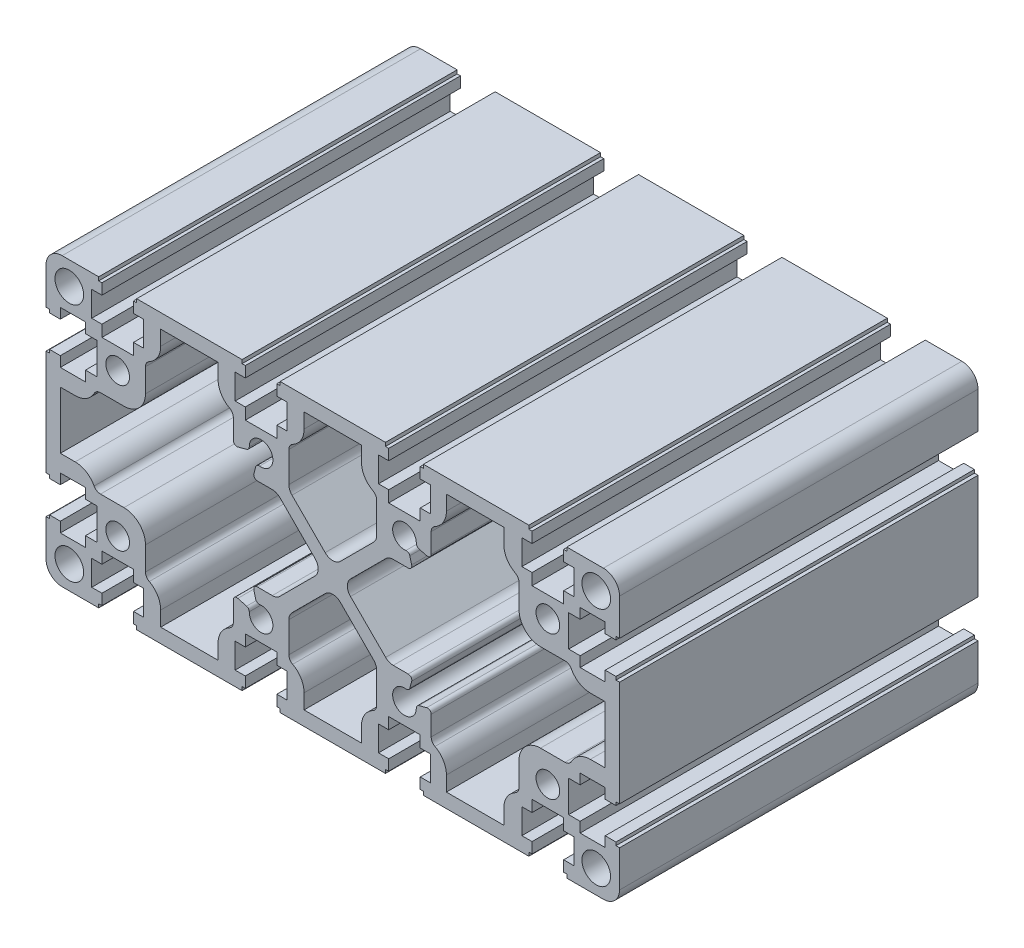
SolidWorks part; units mm, degrees
ref_plane "前视基准面" through (0, 0, 0) normal (0, 0, 1) x (1, 0, 0)
ref_plane "上视基准面" through (0, 0, 0) normal (0, 1, 0) x (1, 0, 0)
ref_plane "右视基准面" through (0, 0, 0) normal (1, 0, 0) x (0, 0, -1)
sketch "草图1" plane through (0, 0, 0) normal (0, 0, 1) x (1, 0, 0)
  line L0 (2688.5545, -1547.2016) -> (2680.1545, -1547.2016)
  line L1 (2558.3545, -1547.2016) -> (2587.7545, -1547.2016)
  line L2 (2537.5545, -1547.2016) -> (2547.7545, -1547.2016)
  line L3 (2533.0545, -1561.9016) -> (2533.0545, -1551.7016)
  line L4 (2533.0545, -1572.5016) -> (2533.0545, -1587.2016)
  line L5 (2548.6545, -1561.4016) -> (2557.4545, -1561.4016)
  line L6 (2557.4545, -1551.2016) -> (2560.3045, -1551.2016)
  line L7 (2548.6545, -1551.2016) -> (2545.8045, -1551.2016)
  line L8 (2558.3545, -1548.2016) -> (2557.4545, -1548.2016)
  line L9 (2548.6545, -1548.2016) -> (2547.7545, -1548.2016)
  line L10 (2548.6545, -1548.2016) -> (2548.6545, -1551.2016)
  line L11 (2557.4545, -1548.2016) -> (2557.4545, -1551.2016)
  line L12 (2547.7545, -1547.2016) -> (2547.7545, -1548.2016)
  line L13 (2558.3545, -1547.2016) -> (2558.3545, -1548.2016)
  line L14 (2545.8045, -1551.2016) -> (2545.8045, -1558.2016)
  line L15 (2560.3045, -1551.2016) -> (2560.3045, -1558.2016)
  line L16 (2545.8045, -1558.2016) -> (2548.6545, -1558.2016)
  line L17 (2557.4545, -1558.2016) -> (2560.3045, -1558.2016)
  line L18 (2557.4545, -1561.4016) -> (2557.4545, -1558.2016)
  line L19 (2548.6545, -1561.4016) -> (2548.6545, -1558.2016)
  line L20 (2592.0077, -1574.4016) -> (2597.426, -1574.4016)
  line L21 (2667.1545, -1547.2016) -> (2638.3545, -1547.2016)
  line L22 (2688.5545, -1547.2016) -> (2678.3545, -1547.2016)
  line L23 (2667.7545, -1547.2016) -> (2638.3545, -1547.2016)
  line L24 (2677.4545, -1561.4016) -> (2668.6545, -1561.4016)
  line L25 (2668.6545, -1551.2016) -> (2665.8045, -1551.2016)
  line L26 (2677.4545, -1551.2016) -> (2680.3045, -1551.2016)
  line L27 (2667.7545, -1548.2016) -> (2668.6545, -1548.2016)
  line L28 (2677.4545, -1548.2016) -> (2678.3545, -1548.2016)
  line L29 (2677.4545, -1548.2016) -> (2677.4545, -1551.2016)
  line L30 (2668.6545, -1548.2016) -> (2668.6545, -1551.2016)
  line L31 (2678.3545, -1547.2016) -> (2678.3545, -1548.2016)
  line L32 (2667.7545, -1547.2016) -> (2667.7545, -1548.2016)
  line L33 (2680.3045, -1551.2016) -> (2680.3045, -1558.2016)
  line L34 (2665.8045, -1551.2016) -> (2665.8045, -1558.2016)
  line L35 (2680.3045, -1558.2016) -> (2677.4545, -1558.2016)
  line L36 (2668.6545, -1558.2016) -> (2665.8045, -1558.2016)
  line L37 (2668.6545, -1561.4016) -> (2668.6545, -1558.2016)
  line L38 (2677.4545, -1561.4016) -> (2677.4545, -1558.2016)
  line L39 (2598.3545, -1547.2016) -> (2627.7545, -1547.2016)
  line L40 (2565.0545, -1551.2016) -> (2581.0545, -1551.2016)
  line L41 (2560.8045, -1568.9516) -> (2560.8045, -1562.4016)
  line L42 (2565.0545, -1555.335) -> (2565.0545, -1551.2016)
  line L43 (2585.3045, -1567.952) -> (2585.3045, -1562.4016)
  line L44 (2581.0545, -1555.335) -> (2581.0545, -1551.2016)
  line L45 (2547.2545, -1571.6016) -> (2547.2545, -1562.8016)
  line L46 (2537.0545, -1562.8016) -> (2537.0545, -1559.9516)
  line L47 (2537.0545, -1571.6016) -> (2537.0545, -1574.4516)
  line L48 (2534.0545, -1561.9016) -> (2534.0545, -1562.8016)
  line L49 (2534.0545, -1571.6016) -> (2534.0545, -1572.5016)
  line L50 (2534.0545, -1571.6016) -> (2537.0545, -1571.6016)
  line L51 (2534.0545, -1562.8016) -> (2537.0545, -1562.8016)
  line L52 (2533.0545, -1572.5016) -> (2534.0545, -1572.5016)
  line L53 (2533.0545, -1561.9016) -> (2534.0545, -1561.9016)
  line L54 (2537.0545, -1574.4516) -> (2544.0545, -1574.4516)
  line L55 (2537.0545, -1559.9516) -> (2544.0545, -1559.9516)
  line L56 (2544.0545, -1574.4516) -> (2544.0545, -1571.6016)
  line L57 (2544.0545, -1562.8016) -> (2544.0545, -1559.9516)
  line L58 (2547.2545, -1562.8016) -> (2544.0545, -1562.8016)
  line L59 (2547.2545, -1571.6016) -> (2544.0545, -1571.6016)
  line L60 (2537.0545, -1587.2016) -> (2537.0545, -1579.2016)
  line L61 (2554.8045, -1574.9516) -> (2548.2545, -1574.9516)
  line L62 (2541.1878, -1579.2016) -> (2537.0545, -1579.2016)
  line L63 (2610.226, -1587.2016) -> (2597.426, -1600.0016)
  line L64 (2613.0545, -1584.3732) -> (2625.3045, -1572.1232)
  line L65 (2628.6829, -1574.4016) -> (2615.8829, -1587.2016)
  line L66 (2613.0545, -1590.03) -> (2600.8045, -1602.28)
  line L67 (2610.226, -1587.2016) -> (2597.426, -1574.4016)
  line L68 (2613.0545, -1590.03) -> (2625.3045, -1602.28)
  line L69 (2613.0545, -1584.3732) -> (2600.8045, -1572.1232)
  line L70 (2615.8829, -1587.2016) -> (2628.6829, -1600.0016)
  line L71 (2693.0545, -1572.5016) -> (2693.0545, -1587.2016)
  line L72 (2665.0045, -1568.9516) -> (2665.0045, -1562.4016)
  line L73 (2678.8545, -1571.6016) -> (2678.8545, -1562.8016)
  line L74 (2689.0545, -1562.8016) -> (2689.0545, -1559.9516)
  line L75 (2689.0545, -1571.6016) -> (2689.0545, -1574.4516)
  line L76 (2692.0545, -1561.9016) -> (2692.0545, -1562.8016)
  line L77 (2692.0545, -1571.6016) -> (2692.0545, -1572.5016)
  line L78 (2692.0545, -1571.6016) -> (2689.0545, -1571.6016)
  line L79 (2692.0545, -1562.8016) -> (2689.0545, -1562.8016)
  line L80 (2693.0545, -1572.5016) -> (2692.0545, -1572.5016)
  line L81 (2693.0545, -1561.9016) -> (2692.0545, -1561.9016)
  line L82 (2689.0545, -1574.4516) -> (2682.0545, -1574.4516)
  line L83 (2689.0545, -1559.9516) -> (2682.0545, -1559.9516)
  line L84 (2682.0545, -1574.4516) -> (2682.0545, -1571.6016)
  line L85 (2682.0545, -1562.8016) -> (2682.0545, -1559.9516)
  line L86 (2678.8545, -1562.8016) -> (2682.0545, -1562.8016)
  line L87 (2678.8545, -1571.6016) -> (2682.0545, -1571.6016)
  line L88 (2689.0545, -1587.2016) -> (2689.0545, -1579.2016)
  line L89 (2671.0045, -1574.9516) -> (2677.8545, -1574.9516)
  line L90 (2684.9211, -1579.2016) -> (2689.0545, -1579.2016)
  line L91 (2693.0545, -1551.7016) -> (2693.0545, -1561.9016)
  line L92 (2589.0143, -1568.2611) -> (2586.5633, -1568.9179)
  line L93 (2591.5596, -1571.2101) -> (2591.0418, -1573.1428)
  line L94 (2634.1012, -1574.4016) -> (2628.6829, -1574.4016)
  line L95 (2637.0946, -1568.2611) -> (2639.2457, -1568.8375)
  line L96 (2634.5493, -1571.2101) -> (2635.0672, -1573.1428)
  line L97 (2605.0545, -1551.2016) -> (2621.0545, -1551.2016)
  line L98 (2600.8045, -1572.1232) -> (2600.8045, -1562.4016)
  line L99 (2605.0545, -1555.335) -> (2605.0545, -1551.2016)
  line L100 (2625.3045, -1572.1232) -> (2625.3045, -1562.4016)
  line L101 (2621.0545, -1555.335) -> (2621.0545, -1551.2016)
  line L102 (2644.7545, -1551.2016) -> (2660.7545, -1551.2016)
  line L103 (2640.5045, -1567.8716) -> (2640.5045, -1562.4016)
  line L104 (2644.7545, -1555.335) -> (2644.7545, -1551.2016)
  line L105 (2660.7545, -1555.335) -> (2660.7545, -1551.2016)
  line L106 (2588.6545, -1561.4016) -> (2597.4545, -1561.4016)
  line L107 (2597.4545, -1551.2016) -> (2600.3045, -1551.2016)
  line L108 (2588.6545, -1551.2016) -> (2585.8045, -1551.2016)
  line L109 (2598.3545, -1548.2016) -> (2597.4545, -1548.2016)
  line L110 (2588.6545, -1548.2016) -> (2587.7545, -1548.2016)
  line L111 (2588.6545, -1548.2016) -> (2588.6545, -1551.2016)
  line L112 (2597.4545, -1548.2016) -> (2597.4545, -1551.2016)
  line L113 (2587.7545, -1547.2016) -> (2587.7545, -1548.2016)
  line L114 (2598.3545, -1547.2016) -> (2598.3545, -1548.2016)
  line L115 (2585.8045, -1551.2016) -> (2585.8045, -1558.2016)
  line L116 (2600.3045, -1551.2016) -> (2600.3045, -1558.2016)
  line L117 (2585.8045, -1558.2016) -> (2588.6545, -1558.2016)
  line L118 (2597.4545, -1558.2016) -> (2600.3045, -1558.2016)
  line L119 (2597.4545, -1561.4016) -> (2597.4545, -1558.2016)
  line L120 (2588.6545, -1561.4016) -> (2588.6545, -1558.2016)
  line L121 (2628.6545, -1561.4016) -> (2637.4545, -1561.4016)
  line L122 (2637.4545, -1551.2016) -> (2640.3045, -1551.2016)
  line L123 (2628.6545, -1551.2016) -> (2625.8045, -1551.2016)
  line L124 (2638.3545, -1548.2016) -> (2637.4545, -1548.2016)
  line L125 (2628.6545, -1548.2016) -> (2627.7545, -1548.2016)
  line L126 (2628.6545, -1548.2016) -> (2628.6545, -1551.2016)
  line L127 (2637.4545, -1548.2016) -> (2637.4545, -1551.2016)
  line L128 (2627.7545, -1547.2016) -> (2627.7545, -1548.2016)
  line L129 (2638.3545, -1547.2016) -> (2638.3545, -1548.2016)
  line L130 (2625.8045, -1551.2016) -> (2625.8045, -1558.2016)
  line L131 (2640.3045, -1551.2016) -> (2640.3045, -1558.2016)
  line L132 (2625.8045, -1558.2016) -> (2628.6545, -1558.2016)
  line L133 (2637.4545, -1558.2016) -> (2640.3045, -1558.2016)
  line L134 (2637.4545, -1561.4016) -> (2637.4545, -1558.2016)
  line L135 (2628.6545, -1561.4016) -> (2628.6545, -1558.2016)
  line L136 (2688.5545, -1627.2016) -> (2680.1545, -1627.2016)
  line L137 (2558.3545, -1627.2016) -> (2587.7545, -1627.2016)
  line L138 (2537.5545, -1627.2016) -> (2547.7545, -1627.2016)
  line L139 (2533.0545, -1612.5016) -> (2533.0545, -1622.7016)
  line L140 (2533.0545, -1601.9016) -> (2533.0545, -1587.2016)
  line L141 (2548.6545, -1613.0016) -> (2557.4545, -1613.0016)
  line L142 (2557.4545, -1623.2016) -> (2560.3045, -1623.2016)
  line L143 (2548.6545, -1623.2016) -> (2545.8045, -1623.2016)
  line L144 (2558.3545, -1626.2016) -> (2557.4545, -1626.2016)
  line L145 (2548.6545, -1626.2016) -> (2547.7545, -1626.2016)
  line L146 (2548.6545, -1626.2016) -> (2548.6545, -1623.2016)
  line L147 (2557.4545, -1626.2016) -> (2557.4545, -1623.2016)
  line L148 (2547.7545, -1627.2016) -> (2547.7545, -1626.2016)
  line L149 (2558.3545, -1627.2016) -> (2558.3545, -1626.2016)
  line L150 (2545.8045, -1623.2016) -> (2545.8045, -1616.2016)
  line L151 (2560.3045, -1623.2016) -> (2560.3045, -1616.2016)
  line L152 (2545.8045, -1616.2016) -> (2548.6545, -1616.2016)
  line L153 (2557.4545, -1616.2016) -> (2560.3045, -1616.2016)
  line L154 (2557.4545, -1613.0016) -> (2557.4545, -1616.2016)
  line L155 (2548.6545, -1613.0016) -> (2548.6545, -1616.2016)
  line L156 (2592.0077, -1600.0016) -> (2597.426, -1600.0016)
  line L157 (2667.1545, -1627.2016) -> (2638.3545, -1627.2016)
  line L158 (2688.5545, -1627.2016) -> (2678.3545, -1627.2016)
  line L159 (2667.7545, -1627.2016) -> (2638.3545, -1627.2016)
  line L160 (2677.4545, -1613.0016) -> (2668.6545, -1613.0016)
  line L161 (2668.6545, -1623.2016) -> (2665.8045, -1623.2016)
  line L162 (2677.4545, -1623.2016) -> (2680.3045, -1623.2016)
  line L163 (2667.7545, -1626.2016) -> (2668.6545, -1626.2016)
  line L164 (2677.4545, -1626.2016) -> (2678.3545, -1626.2016)
  line L165 (2677.4545, -1626.2016) -> (2677.4545, -1623.2016)
  line L166 (2668.6545, -1626.2016) -> (2668.6545, -1623.2016)
  line L167 (2678.3545, -1627.2016) -> (2678.3545, -1626.2016)
  line L168 (2667.7545, -1627.2016) -> (2667.7545, -1626.2016)
  line L169 (2680.3045, -1623.2016) -> (2680.3045, -1616.2016)
  line L170 (2665.8045, -1623.2016) -> (2665.8045, -1616.2016)
  line L171 (2680.3045, -1616.2016) -> (2677.4545, -1616.2016)
  line L172 (2668.6545, -1616.2016) -> (2665.8045, -1616.2016)
  line L173 (2668.6545, -1613.0016) -> (2668.6545, -1616.2016)
  line L174 (2677.4545, -1613.0016) -> (2677.4545, -1616.2016)
  line L175 (2598.3545, -1627.2016) -> (2627.7545, -1627.2016)
  line L176 (2565.0545, -1623.2016) -> (2581.0545, -1623.2016)
  line L177 (2560.8045, -1605.4516) -> (2560.8045, -1612.0016)
  line L178 (2565.0545, -1619.0682) -> (2565.0545, -1623.2016)
  line L179 (2585.3045, -1606.4512) -> (2585.3045, -1612.0016)
  line L180 (2581.0545, -1619.0682) -> (2581.0545, -1623.2016)
  line L181 (2547.2545, -1602.8016) -> (2547.2545, -1611.6016)
  line L182 (2537.0545, -1611.6016) -> (2537.0545, -1614.4516)
  line L183 (2537.0545, -1602.8016) -> (2537.0545, -1599.9516)
  line L184 (2534.0545, -1612.5016) -> (2534.0545, -1611.6016)
  line L185 (2534.0545, -1602.8016) -> (2534.0545, -1601.9016)
  line L186 (2534.0545, -1602.8016) -> (2537.0545, -1602.8016)
  line L187 (2534.0545, -1611.6016) -> (2537.0545, -1611.6016)
  line L188 (2533.0545, -1601.9016) -> (2534.0545, -1601.9016)
  line L189 (2533.0545, -1612.5016) -> (2534.0545, -1612.5016)
  line L190 (2537.0545, -1599.9516) -> (2544.0545, -1599.9516)
  line L191 (2537.0545, -1614.4516) -> (2544.0545, -1614.4516)
  line L192 (2544.0545, -1599.9516) -> (2544.0545, -1602.8016)
  line L193 (2544.0545, -1611.6016) -> (2544.0545, -1614.4516)
  line L194 (2547.2545, -1611.6016) -> (2544.0545, -1611.6016)
  line L195 (2547.2545, -1602.8016) -> (2544.0545, -1602.8016)
  line L196 (2537.0545, -1587.2016) -> (2537.0545, -1595.2016)
  line L197 (2554.8045, -1599.4516) -> (2548.2545, -1599.4516)
  line L198 (2541.1878, -1595.2016) -> (2537.0545, -1595.2016)
  line L199 (2613.0545, -1590.03) -> (2625.3045, -1602.28)
  line L200 (2628.6829, -1600.0016) -> (2615.8829, -1587.2016)
  line L201 (2610.226, -1587.2016) -> (2597.426, -1600.0016)
  line L202 (2613.0545, -1590.03) -> (2600.8045, -1602.28)
  line L203 (2693.0545, -1601.9016) -> (2693.0545, -1587.2016)
  line L204 (2665.0045, -1605.4516) -> (2665.0045, -1612.0016)
  line L205 (2678.8545, -1602.8016) -> (2678.8545, -1611.6016)
  line L206 (2689.0545, -1611.6016) -> (2689.0545, -1614.4516)
  line L207 (2689.0545, -1602.8016) -> (2689.0545, -1599.9516)
  line L208 (2692.0545, -1612.5016) -> (2692.0545, -1611.6016)
  line L209 (2692.0545, -1602.8016) -> (2692.0545, -1601.9016)
  line L210 (2692.0545, -1602.8016) -> (2689.0545, -1602.8016)
  line L211 (2692.0545, -1611.6016) -> (2689.0545, -1611.6016)
  line L212 (2693.0545, -1601.9016) -> (2692.0545, -1601.9016)
  line L213 (2693.0545, -1612.5016) -> (2692.0545, -1612.5016)
  line L214 (2689.0545, -1599.9516) -> (2682.0545, -1599.9516)
  line L215 (2689.0545, -1614.4516) -> (2682.0545, -1614.4516)
  line L216 (2682.0545, -1599.9516) -> (2682.0545, -1602.8016)
  line L217 (2682.0545, -1611.6016) -> (2682.0545, -1614.4516)
  line L218 (2678.8545, -1611.6016) -> (2682.0545, -1611.6016)
  line L219 (2678.8545, -1602.8016) -> (2682.0545, -1602.8016)
  line L220 (2689.0545, -1587.2016) -> (2689.0545, -1595.2016)
  line L221 (2671.0045, -1599.4516) -> (2677.8545, -1599.4516)
  line L222 (2684.9211, -1595.2016) -> (2689.0545, -1595.2016)
  line L223 (2693.0545, -1622.7016) -> (2693.0545, -1612.5016)
  line L224 (2589.0143, -1606.1421) -> (2586.5633, -1605.4853)
  line L225 (2591.5596, -1603.1931) -> (2591.0418, -1601.2604)
  line L226 (2634.1012, -1600.0016) -> (2628.6829, -1600.0016)
  line L227 (2637.0946, -1606.1421) -> (2639.2457, -1605.5657)
  line L228 (2634.5493, -1603.1931) -> (2635.0672, -1601.2604)
  line L229 (2605.0545, -1623.2016) -> (2621.0545, -1623.2016)
  line L230 (2600.8045, -1602.28) -> (2600.8045, -1612.0016)
  line L231 (2605.0545, -1619.0682) -> (2605.0545, -1623.2016)
  line L232 (2625.3045, -1602.28) -> (2625.3045, -1612.0016)
  line L233 (2621.0545, -1619.0682) -> (2621.0545, -1623.2016)
  line L234 (2644.7545, -1623.2016) -> (2660.7545, -1623.2016)
  line L235 (2640.5045, -1606.5316) -> (2640.5045, -1612.0016)
  line L236 (2644.7545, -1619.0682) -> (2644.7545, -1623.2016)
  line L237 (2660.7545, -1619.0682) -> (2660.7545, -1623.2016)
  line L238 (2588.6545, -1613.0016) -> (2597.4545, -1613.0016)
  line L239 (2597.4545, -1623.2016) -> (2600.3045, -1623.2016)
  line L240 (2588.6545, -1623.2016) -> (2585.8045, -1623.2016)
  line L241 (2598.3545, -1626.2016) -> (2597.4545, -1626.2016)
  line L242 (2588.6545, -1626.2016) -> (2587.7545, -1626.2016)
  line L243 (2588.6545, -1626.2016) -> (2588.6545, -1623.2016)
  line L244 (2597.4545, -1626.2016) -> (2597.4545, -1623.2016)
  line L245 (2587.7545, -1627.2016) -> (2587.7545, -1626.2016)
  line L246 (2598.3545, -1627.2016) -> (2598.3545, -1626.2016)
  line L247 (2585.8045, -1623.2016) -> (2585.8045, -1616.2016)
  line L248 (2600.3045, -1623.2016) -> (2600.3045, -1616.2016)
  line L249 (2585.8045, -1616.2016) -> (2588.6545, -1616.2016)
  line L250 (2597.4545, -1616.2016) -> (2600.3045, -1616.2016)
  line L251 (2597.4545, -1613.0016) -> (2597.4545, -1616.2016)
  line L252 (2588.6545, -1613.0016) -> (2588.6545, -1616.2016)
  line L253 (2628.6545, -1613.0016) -> (2637.4545, -1613.0016)
  line L254 (2637.4545, -1623.2016) -> (2640.3045, -1623.2016)
  line L255 (2628.6545, -1623.2016) -> (2625.8045, -1623.2016)
  line L256 (2638.3545, -1626.2016) -> (2637.4545, -1626.2016)
  line L257 (2628.6545, -1626.2016) -> (2627.7545, -1626.2016)
  line L258 (2628.6545, -1626.2016) -> (2628.6545, -1623.2016)
  line L259 (2637.4545, -1626.2016) -> (2637.4545, -1623.2016)
  line L260 (2627.7545, -1627.2016) -> (2627.7545, -1626.2016)
  line L261 (2638.3545, -1627.2016) -> (2638.3545, -1626.2016)
  line L262 (2625.8045, -1623.2016) -> (2625.8045, -1616.2016)
  line L263 (2640.3045, -1623.2016) -> (2640.3045, -1616.2016)
  line L264 (2625.8045, -1616.2016) -> (2628.6545, -1616.2016)
  line L265 (2637.4545, -1616.2016) -> (2640.3045, -1616.2016)
  line L266 (2637.4545, -1613.0016) -> (2637.4545, -1616.2016)
  line L267 (2628.6545, -1613.0016) -> (2628.6545, -1616.2016)
  arc A0 (2693.0545, -1551.7016) -> (2688.5545, -1547.2016) centre (2688.5545, -1551.7016) ccw
  arc A1 (2537.5545, -1547.2016) -> (2533.0545, -1551.7016) centre (2537.5545, -1551.7016) ccw
  arc A2 (2591.0418, -1573.1428) -> (2592.0077, -1574.4016) centre (2592.0077, -1573.4016) ccw
  arc A3 (2554.8045, -1574.9516) -> (2560.8045, -1568.9516) centre (2554.8045, -1568.9516) ccw
  arc A4 (2561.867, -1560.6349) -> (2560.8045, -1562.4016) centre (2562.8045, -1562.4016) ccw
  arc A5 (2561.867, -1560.6349) -> (2565.0545, -1555.335) centre (2559.0545, -1555.335) ccw
  arc A6 (2585.3045, -1562.4016) -> (2584.242, -1560.6349) centre (2583.3045, -1562.4016) ccw
  arc A7 (2581.0545, -1555.335) -> (2584.242, -1560.6349) centre (2587.0545, -1555.335) ccw
  arc A8 (2548.2545, -1574.9516) -> (2546.4878, -1576.0141) centre (2548.2545, -1576.9516) ccw
  arc A9 (2541.1878, -1579.2016) -> (2546.4878, -1576.0141) centre (2541.1878, -1573.2016) ccw
  arc A10 (2665.0045, -1568.9516) -> (2671.0045, -1574.9516) centre (2671.0045, -1568.9516) ccw
  arc A11 (2679.6211, -1576.0141) -> (2677.8545, -1574.9516) centre (2677.8545, -1576.9516) ccw
  arc A12 (2679.6211, -1576.0141) -> (2684.9211, -1579.2016) centre (2684.9211, -1573.2016) ccw
  circle A13 centre (2553.0545, -1567.2016) radius 3.3
  arc A14 (2592.6486, -1570.4765) -> (2589.7553, -1567.2734) centre (2593.0545, -1567.2016) ccw
  arc A15 (2589.0143, -1568.2611) -> (2589.7553, -1567.2734) centre (2588.7555, -1567.2952) ccw
  arc A16 (2592.6486, -1570.4765) -> (2591.5596, -1571.2101) centre (2592.5256, -1571.4689) ccw
  arc A17 (2585.3045, -1567.952) -> (2586.5633, -1568.9179) centre (2586.3045, -1567.952) ccw
  arc A18 (2634.1012, -1574.4016) -> (2635.0672, -1573.1428) centre (2634.1012, -1573.4016) ccw
  arc A19 (2636.3537, -1567.2734) -> (2633.4604, -1570.4765) centre (2633.0545, -1567.2016) ccw
  arc A20 (2636.3537, -1567.2734) -> (2637.0946, -1568.2611) centre (2637.3535, -1567.2952) ccw
  arc A21 (2634.5493, -1571.2101) -> (2633.4604, -1570.4765) centre (2633.5834, -1571.4689) ccw
  arc A22 (2601.867, -1560.6349) -> (2600.8045, -1562.4016) centre (2602.8045, -1562.4016) ccw
  arc A23 (2601.867, -1560.6349) -> (2605.0545, -1555.335) centre (2599.0545, -1555.335) ccw
  arc A24 (2625.3045, -1562.4016) -> (2624.242, -1560.6349) centre (2623.3045, -1562.4016) ccw
  arc A25 (2621.0545, -1555.335) -> (2624.242, -1560.6349) centre (2627.0545, -1555.335) ccw
  circle A26 centre (2673.0545, -1567.2016) radius 3.3
  arc A27 (2639.2457, -1568.8375) -> (2640.5045, -1567.8716) centre (2639.5045, -1567.8716) ccw
  arc A28 (2641.567, -1560.6349) -> (2640.5045, -1562.4016) centre (2642.5045, -1562.4016) ccw
  arc A29 (2641.567, -1560.6349) -> (2644.7545, -1555.335) centre (2638.7545, -1555.335) ccw
  arc A30 (2665.0045, -1562.4016) -> (2663.942, -1560.6349) centre (2663.0045, -1562.4016) ccw
  arc A31 (2660.7545, -1555.335) -> (2663.942, -1560.6349) centre (2666.7545, -1555.335) ccw
  arc A32 (2688.5545, -1627.2016) -> (2693.0545, -1622.7016) centre (2688.5545, -1622.7016) ccw
  arc A33 (2533.0545, -1622.7016) -> (2537.5545, -1627.2016) centre (2537.5545, -1622.7016) ccw
  arc A34 (2592.0077, -1600.0016) -> (2591.0418, -1601.2604) centre (2592.0077, -1601.0016) ccw
  arc A35 (2560.8045, -1605.4516) -> (2554.8045, -1599.4516) centre (2554.8045, -1605.4516) ccw
  arc A36 (2560.8045, -1612.0016) -> (2561.867, -1613.7683) centre (2562.8045, -1612.0016) ccw
  arc A37 (2565.0545, -1619.0682) -> (2561.867, -1613.7683) centre (2559.0545, -1619.0682) ccw
  arc A38 (2584.242, -1613.7683) -> (2585.3045, -1612.0016) centre (2583.3045, -1612.0016) ccw
  arc A39 (2584.242, -1613.7683) -> (2581.0545, -1619.0682) centre (2587.0545, -1619.0682) ccw
  arc A40 (2546.4878, -1598.3891) -> (2548.2545, -1599.4516) centre (2548.2545, -1597.4516) ccw
  arc A41 (2546.4878, -1598.3891) -> (2541.1878, -1595.2016) centre (2541.1878, -1601.2016) ccw
  arc A42 (2671.0045, -1599.4516) -> (2665.0045, -1605.4516) centre (2671.0045, -1605.4516) ccw
  arc A43 (2677.8545, -1599.4516) -> (2679.6211, -1598.3891) centre (2677.8545, -1597.4516) ccw
  arc A44 (2684.9211, -1595.2016) -> (2679.6211, -1598.3891) centre (2684.9211, -1601.2016) ccw
  circle A45 centre (2553.0545, -1607.2016) radius 3.3
  arc A46 (2589.7553, -1607.1298) -> (2592.6486, -1603.9267) centre (2593.0545, -1607.2016) ccw
  arc A47 (2589.7553, -1607.1298) -> (2589.0143, -1606.1421) centre (2588.7555, -1607.108) ccw
  arc A48 (2591.5596, -1603.1931) -> (2592.6486, -1603.9267) centre (2592.5256, -1602.9343) ccw
  arc A49 (2586.5633, -1605.4853) -> (2585.3045, -1606.4512) centre (2586.3045, -1606.4512) ccw
  arc A50 (2635.0672, -1601.2604) -> (2634.1012, -1600.0016) centre (2634.1012, -1601.0016) ccw
  arc A51 (2633.4604, -1603.9267) -> (2636.3537, -1607.1298) centre (2633.0545, -1607.2016) ccw
  arc A52 (2637.0946, -1606.1421) -> (2636.3537, -1607.1298) centre (2637.3535, -1607.108) ccw
  arc A53 (2633.4604, -1603.9267) -> (2634.5493, -1603.1931) centre (2633.5834, -1602.9343) ccw
  arc A54 (2600.8045, -1612.0016) -> (2601.867, -1613.7683) centre (2602.8045, -1612.0016) ccw
  arc A55 (2605.0545, -1619.0682) -> (2601.867, -1613.7683) centre (2599.0545, -1619.0682) ccw
  arc A56 (2624.242, -1613.7683) -> (2625.3045, -1612.0016) centre (2623.3045, -1612.0016) ccw
  arc A57 (2624.242, -1613.7683) -> (2621.0545, -1619.0682) centre (2627.0545, -1619.0682) ccw
  circle A58 centre (2673.0545, -1607.2016) radius 3.3
  arc A59 (2640.5045, -1606.5316) -> (2639.2457, -1605.5657) centre (2639.5045, -1606.5316) ccw
  arc A60 (2640.5045, -1612.0016) -> (2641.567, -1613.7683) centre (2642.5045, -1612.0016) ccw
  arc A61 (2644.7545, -1619.0682) -> (2641.567, -1613.7683) centre (2638.7545, -1619.0682) ccw
  arc A62 (2663.942, -1613.7683) -> (2665.0045, -1612.0016) centre (2663.0045, -1612.0016) ccw
  arc A63 (2663.942, -1613.7683) -> (2660.7545, -1619.0682) centre (2666.7545, -1619.0682) ccw
  circle A64 centre (2539.5545, -1553.7016) radius 4
  circle A65 centre (2539.5545, -1620.7016) radius 4
  circle A66 centre (2686.5545, -1620.7016) radius 4
  circle A67 centre (2686.5545, -1553.7016) radius 4
extrude "凸台-拉伸1" add sketch "草图1" along normal blind 100 contours L139 A33 L138 L148 L145 L146 L143 L150 L152 L155 L141 L154 L153 L151 L142 L147 L144 L149 L137 L245 L242 L243 L240 L247 L249 L252 L238 L251 L250 L248 L239 L244 L241 L246 L175 L260 L257 L258 L255 L262 L264 L267 L253 L266 L265 L263 L254 L259 L256 L261 L157
fillet "圆角1" radius 3 12 edges at (2628.6829, -1574.4016, 50) (2628.6829, -1600.0016, 50) (2615.8829, -1587.2016, 50) (2597.426, -1600.0016, 50) (2597.426, -1574.4016, 50) (2610.226, -1587.2016, 50) (2625.3045, -1602.28, 50) (2600.8045, -1602.28, 50) (2613.0545, -1590.03, 50) (2613.0545, -1584.3732, 50) (2600.8045, -1572.1232, 50) (2625.3045, -1572.1232, 50)
